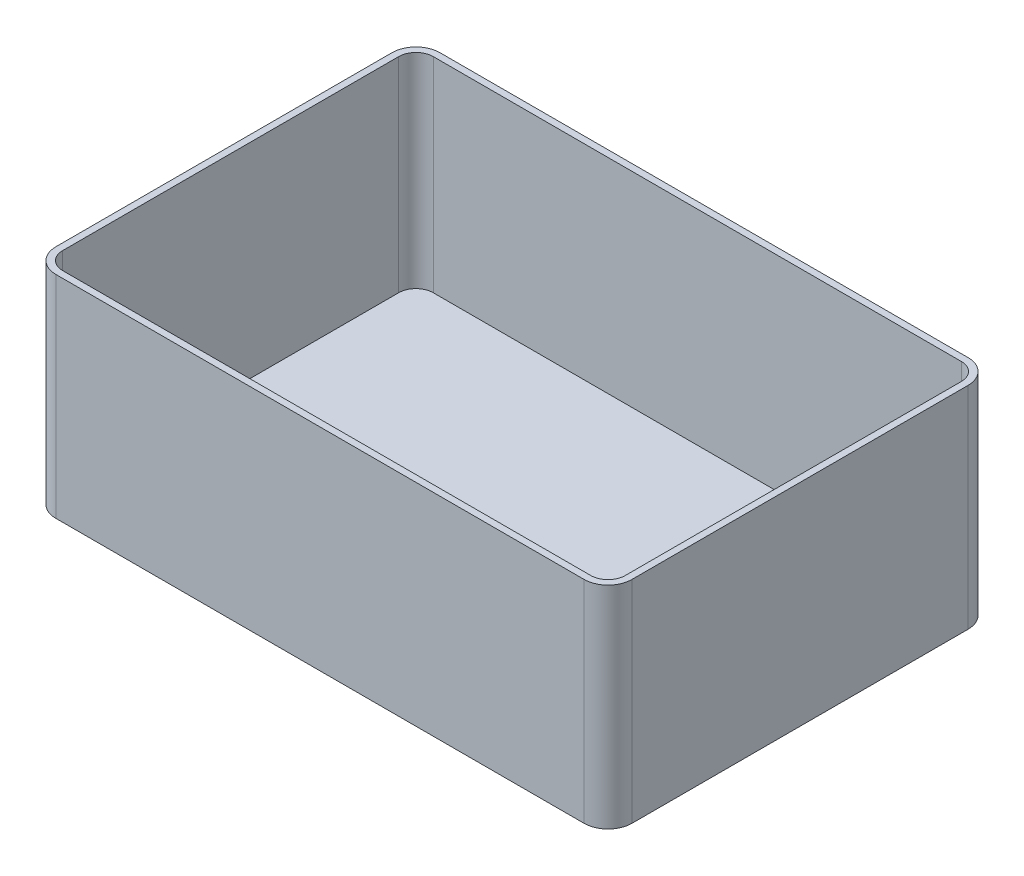
SolidWorks part; units mm, degrees
ref_plane "Front Plane" through (0, 0, 0) normal (0, 0, 1) x (1, 0, 0)
ref_plane "Top Plane" through (0, 0, 0) normal (0, 1, 0) x (1, 0, 0)
ref_plane "Right Plane" through (0, 0, 0) normal (1, 0, 0) x (0, 0, -1)
sketch "Sketch1" plane through (0, 0, 0) normal (0, 1, 0) x (1, 0, 0)
  line L1 (-275, -200) -> (275, -200)
  line L2 (-300, -175) -> (-300, 175)
  line L3 (-275, 200) -> (275, 200)
  line L4 (300, -175) -> (300, 175)
  line L5 (-300, -200) -> (300, 200) construction
  line L6 (-300, 200) -> (300, -200) construction
  arc A0 (275, 200) -> (300, 175) centre (275, 175) cw
  arc A1 (275, -200) -> (300, -175) centre (275, -175) ccw
  arc A2 (-275, -200) -> (-300, -175) centre (-275, -175) cw
  arc A3 (-300, 175) -> (-275, 200) centre (-275, 175) cw
  point P0 (0, 0)
  dimension "D3" = 25
  dimension "D1" = 600
  dimension "D2" = 400
extrude "Boss-Extrude1" add sketch "Sketch1" along normal blind 220
shell "Shell1" thickness 7
